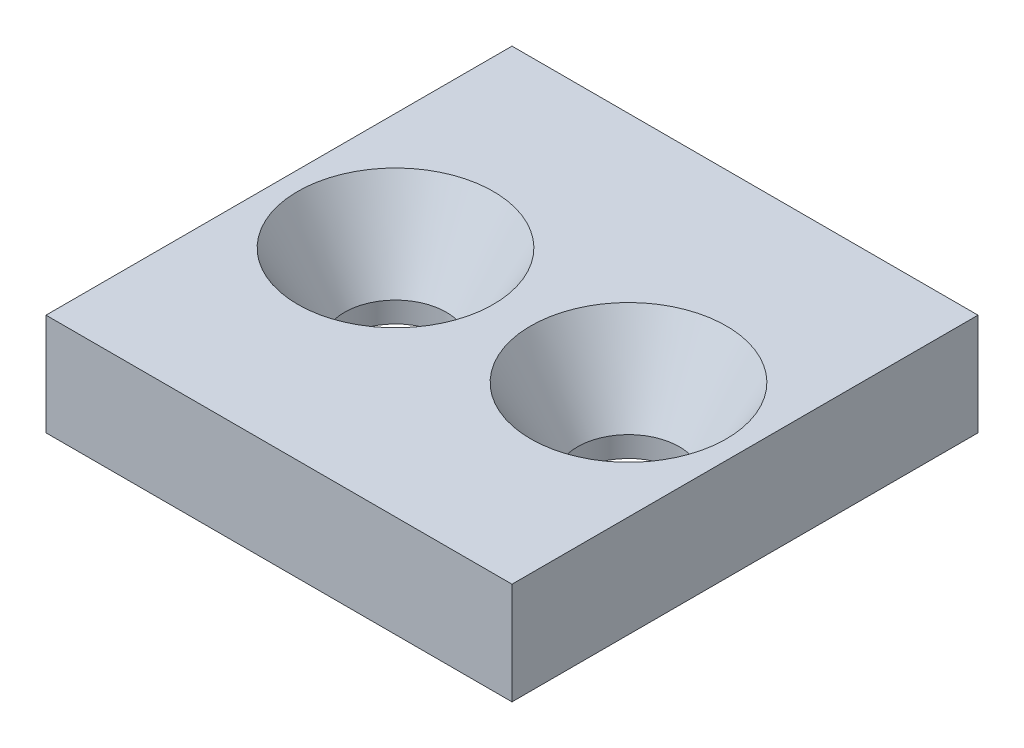
SolidWorks part; units mm, degrees
ref_plane "Front Plane" through (0, 0, 0) normal (0, 0, 1) x (1, 0, 0)
ref_plane "Top Plane" through (0, 0, 0) normal (0, 1, 0) x (1, 0, 0)
ref_plane "Right Plane" through (0, 0, 0) normal (1, 0, 0) x (0, 0, -1)
sketch "Sketch1" plane through (0, 0, 0) normal (0, 1, 0) x (1, 0, 0)
  line L0 (0, 0) -> (0, 32)
  line L1 (0, 0) -> (32, 0)
  line L2 (0, 32) -> (32, 32)
  line L3 (32, 32) -> (32, 0)
  line L4 (0, 16) -> (8, 16) construction
  line L5 (8, 16) -> (24, 16) construction
  line L6 (24, 16) -> (32, 16) construction
  dimension "D1" = 32
  dimension "D2" = 8
extrude "Boss-Extrude1" add sketch "Sketch1" along normal blind 7
hole_wizard "CSK for M6 SFHCS1" positions "Sketch3" profile "Sketch4" countersink size "M6" standard "ANSI Metric" end condition through all
sketch "Sketch3" plane through (0, 7, 0) normal (0, 1, 0) x (1, 0, 0)
  point P0 (8, 16)
  point P3 (24, 16)
sketch "Sketch4" plane through (8, 7, -16) normal (1, 0, 0) x (0, 0, 1)
  line L0 (0, 0) -> (0, 7)
  line L1 (0, 7) -> (3.5, 7)
  line L2 (3.5, 7) -> (3.5, 5.5772)
  line L3 (3.5, 5.5772) -> (6.72, 0)
  line L5 (6.72, 0) -> (0, 0)
  line L6 (-3.5, 5.5772) -> (-6.72, 0) construction
  line L11 (0, -6.35) -> (0, 107.95) construction
  dimension "Thru Hole Dia." = 7
  dimension "Thru Hole Depth" = 7
  dimension "Near C'Sink Dia." = 13.44
  dimension "Near C'Sink Angle" = 60
